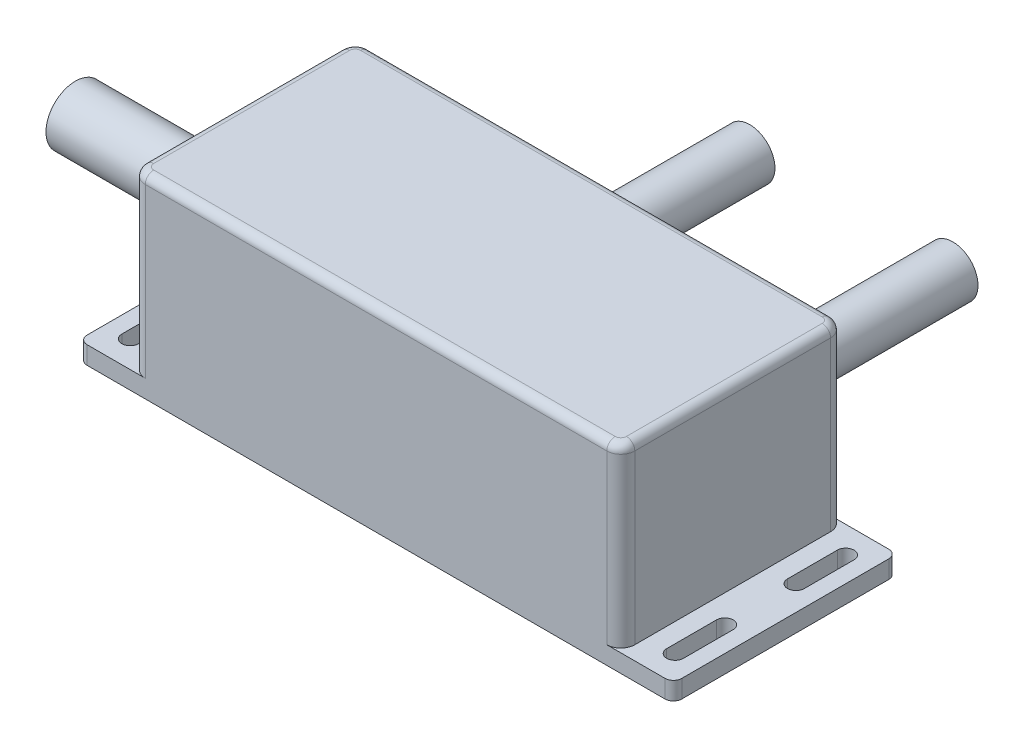
SolidWorks part; units mm, degrees
ref_plane "Ebene vorne" through (0, 0, 0) normal (0, 0, 1) x (1, 0, 0)
ref_plane "Ebene oben" through (0, 0, 0) normal (0, 1, 0) x (1, 0, 0)
ref_plane "Ebene rechts" through (0, 0, 0) normal (1, 0, 0) x (0, 0, -1)
sketch "Skizze1" plane through (0, 0, 0) normal (0, 1, 0) x (1, 0, 0)
  line L0 (-145.0513, 0) -> (142.7515, 0) construction
  line L1 (0, 83.5318) -> (0, -71.3758) construction
  line L2 (-106.3, -37) -> (-106.3, 37)
  line L3 (-103.3, 40) -> (103.3, 40)
  line L4 (106.3, -37) -> (106.3, 37)
  line L5 (-103.3, -40) -> (103.3, -40)
  line L6 (-97.4, 81.9443) -> (-97.4, -61.6577) construction
  line L7 (-97.4, 30.5) -> (-97.4, 12.7) construction
  line L8 (-94.4, 30.5) -> (-94.4, 12.7)
  line L9 (-100.4, 30.5) -> (-100.4, 12.7)
  line L10 (-97.4, -30.5) -> (-97.4, -12.7) construction
  line L11 (-94.4, -30.5) -> (-94.4, -12.7)
  line L12 (-100.4, -30.5) -> (-100.4, -12.7)
  line L13 (97.4, 30.5) -> (97.4, 12.7) construction
  line L14 (94.4, 30.5) -> (94.4, 12.7)
  line L15 (100.4, 30.5) -> (100.4, 12.7)
  line L16 (97.4, -30.5) -> (97.4, -12.7) construction
  line L17 (94.4, -30.5) -> (94.4, -12.7)
  line L18 (100.4, -30.5) -> (100.4, -12.7)
  arc A0 (-94.4, 30.5) -> (-100.4, 30.5) centre (-97.4, 30.5) ccw
  arc A1 (-100.4, 12.7) -> (-94.4, 12.7) centre (-97.4, 12.7) ccw
  arc A2 (-94.4, -30.5) -> (-100.4, -30.5) centre (-97.4, -30.5) cw
  arc A3 (-100.4, -12.7) -> (-94.4, -12.7) centre (-97.4, -12.7) cw
  arc A4 (94.4, 30.5) -> (100.4, 30.5) centre (97.4, 30.5) cw
  arc A5 (100.4, 12.7) -> (94.4, 12.7) centre (97.4, 12.7) cw
  arc A6 (94.4, -30.5) -> (100.4, -30.5) centre (97.4, -30.5) ccw
  arc A7 (100.4, -12.7) -> (94.4, -12.7) centre (97.4, -12.7) ccw
  arc A8 (-103.3, 40) -> (-106.3, 37) centre (-103.3, 37) ccw
  arc A9 (-106.3, -37) -> (-103.3, -40) centre (-103.3, -37) ccw
  arc A10 (103.3, -40) -> (106.3, -37) centre (103.3, -37) ccw
  arc A11 (106.3, 37) -> (103.3, 40) centre (103.3, 37) ccw
  point P9 (0, 40)
  point P10 (0, -40)
  point P12 (106.3, 0)
  point P13 (-106.3, 0)
  point P17 (-97.4, 21.6)
  point P22 (-94.4, 21.6)
  point P25 (-97.4, -21.6)
  point P32 (97.4, 21.6)
  point P39 (97.4, -21.6)
  point P46 (-106.3, 40)
  point P49 (-106.3, -40)
  point P52 (106.3, -40)
  point P55 (106.3, 40)
  dimension "D7" = 3
  dimension "D1" = 80
  dimension "D2" = 212.6
  dimension "D3" = 6
  dimension "D4" = 17.8
  dimension "D5" = 43.2
  dimension "D6" = 8.9
extrude "Aufsatz-Linear austragen1" add sketch "Skizze1" along normal blind 6.4
sketch "Skizze2" plane through (0, 6.4, 0) normal (0, 1, 0) x (1, 0, 0)
  line L0 (145.5519, 0) -> (-137.5042, 0) construction
  line L1 (0, -77.596) -> (0, 68.5536) construction
  line L2 (87.5, 40) -> (87.5, -40)
  line L3 (-103.3, -40) -> (103.3, -40) construction
  line L4 (87.5, -40) -> (-87.5, -40)
  line L5 (-87.5, 40) -> (-87.5, -40)
  line L6 (87.5, 40) -> (-87.5, 40)
  point P10 (0, 40)
  point P12 (0, -40)
  point P14 (-87.5, 0)
  point P15 (87.5, 0)
  dimension "D1" = 175
extrude "Aufsatz-Linear austragen2" add sketch "Skizze2" along normal blind 63
fillet "Verrundung1" radius 5 4 edges at (87.5, 37.9, -40) (-87.5, 37.9, -40) (-87.5, 37.9, 40) (87.5, 37.9, 40)
fillet "Verrundung2" radius 3 8 edges at (86.0355, 69.4, -38.5355) (87.5, 69.4, 0) (86.0355, 69.4, 38.5355) (0, 69.4, 40) (-86.0355, 69.4, 38.5355) (-87.5, 69.4, 0) (-86.0355, 69.4, -38.5355) (0, 69.4, -40)
sketch "Skizze3" plane through (0, 0, -40) normal (0, 0, -1) x (-1, 0, 0)
  line L0 (-126.9977, 34) -> (156.4082, 34) construction
  line L1 (82.5, 0) -> (-82.5, 0) construction
  line L2 (-87.5, 6.4) -> (-87.5, 66.4) construction
  circle A0 centre (-56.2, 34) radius 9
  circle A1 centre (16.4, 34) radius 9
  dimension "D1" = 18
  dimension "D2" = 18
  dimension "D3" = 34
  dimension "D4" = 31.3
  dimension "D5" = 72.6
extrude "Aufsatz-Linear austragen3" add sketch "Skizze3" along normal blind 70
sketch "Skizze4" plane through (-87.5, 0, 0) normal (-1, 0, 0) x (0, 0, 1)
  line L0 (-37, 6.4) -> (37, 6.4) construction
  line L1 (0, -71.3907) -> (0, 81.1881) construction
  circle A0 centre (0, 35.4) radius 10.5
  dimension "D1" = 21
  dimension "D2" = 29
extrude "Aufsatz-Linear austragen4" add sketch "Skizze4" along normal blind 60
